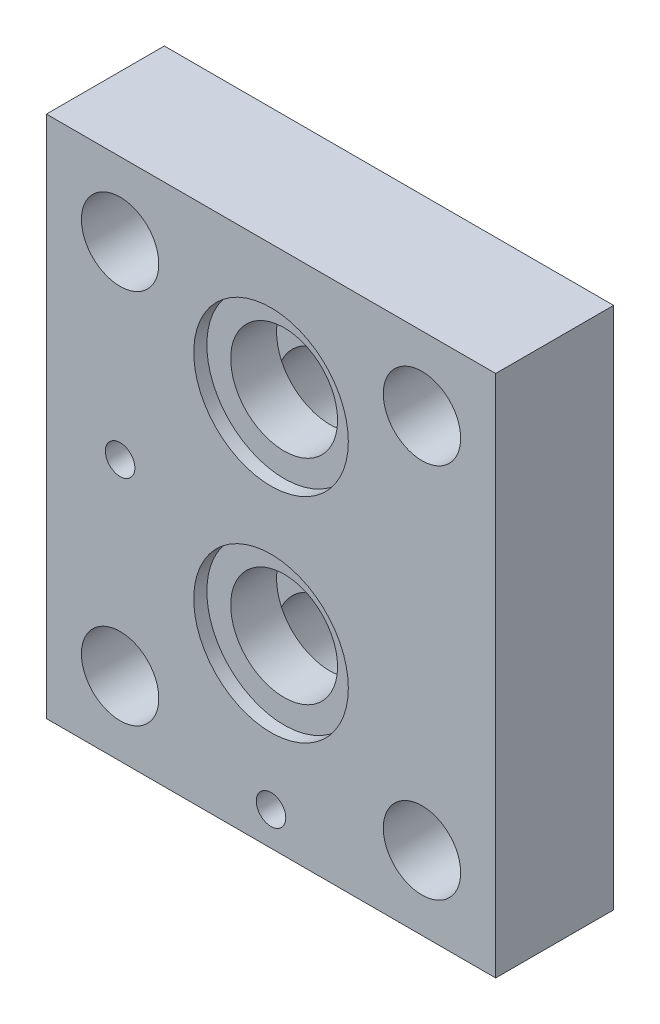
SolidWorks part; units mm, degrees
ref_plane "Front Plane" through (0, 0, 0) normal (1, 0, 0) x (0, 1, 0)
ref_plane "Top Plane" through (0, 0, 0) normal (0, 0, 1) x (0, 1, 0)
ref_plane "Right Plane" through (0, 0, 0) normal (0, 1, 0) x (-1, 0, 0)
sketch "Sketch1" plane through (0, 0, 0) normal (0, 0, 1) x (0, 1, 0)
  line L1 (-56.388, -48.387) -> (56.388, -48.387)
  line L2 (-56.388, -48.387) -> (-56.388, 48.387)
  line L3 (-56.388, 48.387) -> (56.388, 48.387)
  line L4 (56.388, -48.387) -> (56.388, 48.387)
  line L5 (-56.388, -48.387) -> (56.388, 48.387) construction
  line L6 (-56.388, 48.387) -> (56.388, -48.387) construction
  point P0 (0, 0)
extrude "Boss-Extrude1" add sketch "Sketch1" along normal mid plane 25.4
hole_wizard "5/8 Clearance Hole1" positions "Sketch3" profile "Sketch2" hole size "5/8" standard "ANSI Inch"
sketch "Sketch3" plane through (0, 0, -12.7) normal (0, 0, -1) x (-1, 0, 0)
  point P0 (-32.512, -40.513)
sketch "Sketch2" plane through (32.512, -40.513, -12.7) normal (1, 0, 0) x (0, 1, 0)
  line L0 (0, 0) -> (0, 30.4078)
  line L1 (0, 30.4078) -> (8.3344, 25.4)
  line L2 (8.3344, 25.4) -> (8.3344, 0)
  line L5 (8.3344, 0) -> (0, 0)
  line L10 (0, 30.4078) -> (-8.3344, 25.4) construction
  line L11 (0, -6.35) -> (0, 107.95) construction
  dimension "Hole Dia." = 16.6687
  dimension "Hole Depth" = 25.4
  dimension "Drill Angle" = 118
hole_wizard "5/8 Clearance Hole2" positions "Sketch5" profile "Sketch4" hole size "5/8" standard "ANSI Inch"
sketch "Sketch5" plane through (0, 0, -12.7) normal (0, 0, -1) x (-1, 0, 0)
  point P0 (-32.512, 40.513)
  point P1 (32.512, -40.513)
  point P3 (32.512, 40.513)
sketch "Sketch4" plane through (32.512, 40.513, -12.7) normal (1, 0, 0) x (0, 1, 0)
  line L0 (0, 0) -> (0, 30.4078)
  line L1 (0, 30.4078) -> (8.3344, 25.4)
  line L2 (8.3344, 25.4) -> (8.3344, 0)
  line L5 (8.3344, 0) -> (0, 0)
  line L10 (0, 30.4078) -> (-8.3344, 25.4) construction
  line L11 (0, -6.35) -> (0, 107.95) construction
  dimension "Hole Dia." = 16.6687
  dimension "Hole Depth" = 25.4
  dimension "Drill Angle" = 118
sketch "Sketch6" plane through (0, 0, 0) normal (0, 0, 1) x (0, 1, 0)
  circle A0 centre (-27.813, 0) radius 11.5094
extrude "Cut-Extrude2" cut sketch "Sketch6" along normal blind 12.7 from offset 12.7
sketch "Sketch7" plane through (0, 0, 0) normal (0, 0, 1) x (0, 1, 0)
  circle A0 centre (18.161, 0) radius 11.5094
extrude "Cut-Extrude4" cut sketch "Sketch7" along normal blind 12.7 from offset 12.7
sketch "Sketch8" plane through (0, 0, 0) normal (0, 0, 1) x (0, 1, 0)
  circle A0 centre (-18.161, 0) radius 11.5094
extrude "Cut-Extrude6" cut sketch "Sketch8" against normal blind 12.7 from offset 12.7
sketch "Sketch9" plane through (0, 0, 0) normal (0, 0, 1) x (0, 1, 0)
  circle A0 centre (27.813, 0) radius 11.5094
extrude "Cut-Extrude8" cut sketch "Sketch9" against normal blind 12.7 from offset 12.7
sketch "Sketch10" plane through (0, 0, 0) normal (0, 0, 1) x (0, 1, 0)
  circle A0 centre (-18.161, 0) radius 16.6497
extrude "Cut-Extrude10" cut sketch "Sketch10" against normal blind 2.8194 from offset 12.7
sketch "Sketch11" plane through (0, 0, 0) normal (0, 0, 1) x (0, 1, 0)
  circle A0 centre (27.813, 0) radius 16.6497
extrude "Cut-Extrude12" cut sketch "Sketch11" against normal blind 2.8194 from offset 12.7
sketch "Sketch14" plane through (0, 0, 0) normal (0, 0, 1) x (0, 1, 0)
  circle A0 centre (49.149, 0) radius 3.5719
  circle A1 centre (0.127, -32.512) radius 3.5719
extrude "Cut-Extrude14" cut sketch "Sketch14" along normal blind 7.874 from offset 12.7
sketch "Sketch15" plane through (0, 0, 0) normal (0, 0, 1) x (0, 1, 0)
  circle A0 centre (-49.149, 0) radius 3.175
  circle A1 centre (-0.127, 32.512) radius 3.175
extrude "Cut-Extrude16" cut sketch "Sketch15" against normal blind 7.874 from offset 12.7
